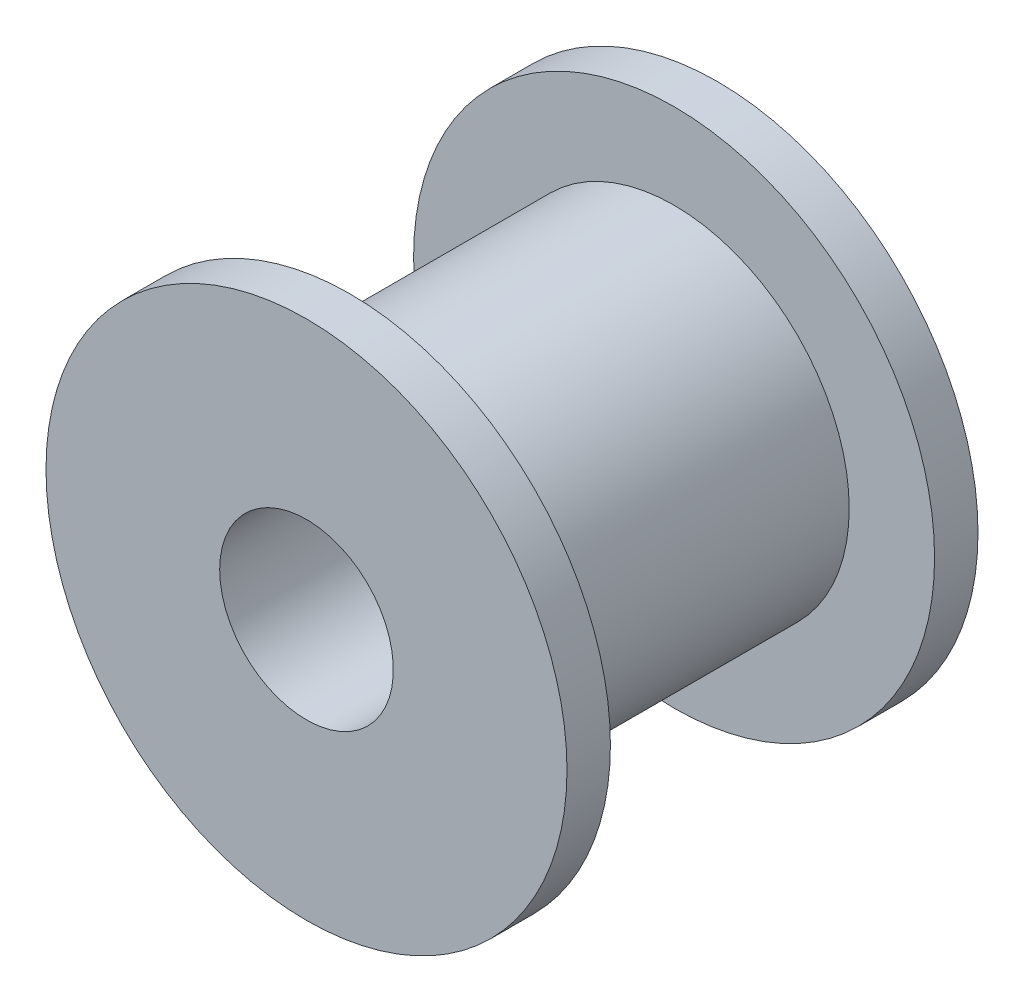
SolidWorks part; units mm, degrees
ref_plane "Front Plane" through (0, 0, 0) normal (0, 0, 1) x (1, 0, 0)
ref_plane "Top Plane" through (0, 0, 0) normal (0, 1, 0) x (1, 0, 0)
ref_plane "Right Plane" through (0, 0, 0) normal (1, 0, 0) x (0, 0, -1)
sketch "Sketch1" plane through (0, 0, 0) normal (0, 1, 0) x (1, 0, 0)
  line L0 (0, 16.2671) -> (0, -12.354) construction
  line L1 (-21.913, 0) -> (14.9255, 0) construction
  line L2 (3, -7.1) -> (3, 7.1)
  line L3 (3, 7.1) -> (9, 7.1)
  line L4 (9, 7.1) -> (9, 5.6)
  line L5 (9, 5.6) -> (6.05, 5.6)
  line L6 (6.05, 5.6) -> (6.05, 0)
  line L7 (6.05, -5.6) -> (6.05, 0)
  line L8 (9, -5.6) -> (6.05, -5.6)
  line L9 (9, -7.1) -> (9, -5.6)
  line L10 (3, -7.1) -> (9, -7.1)
  point P11 (6.05, 2.8)
  point P16 (3, 0)
  dimension "D1" = 9
  dimension "D2" = 3
  dimension "D3" = 6.05
  dimension "D4" = 5.6
  dimension "D5" = 7.1
revolve "Revolve1" add sketch "Sketch1" angle 360 about L0
